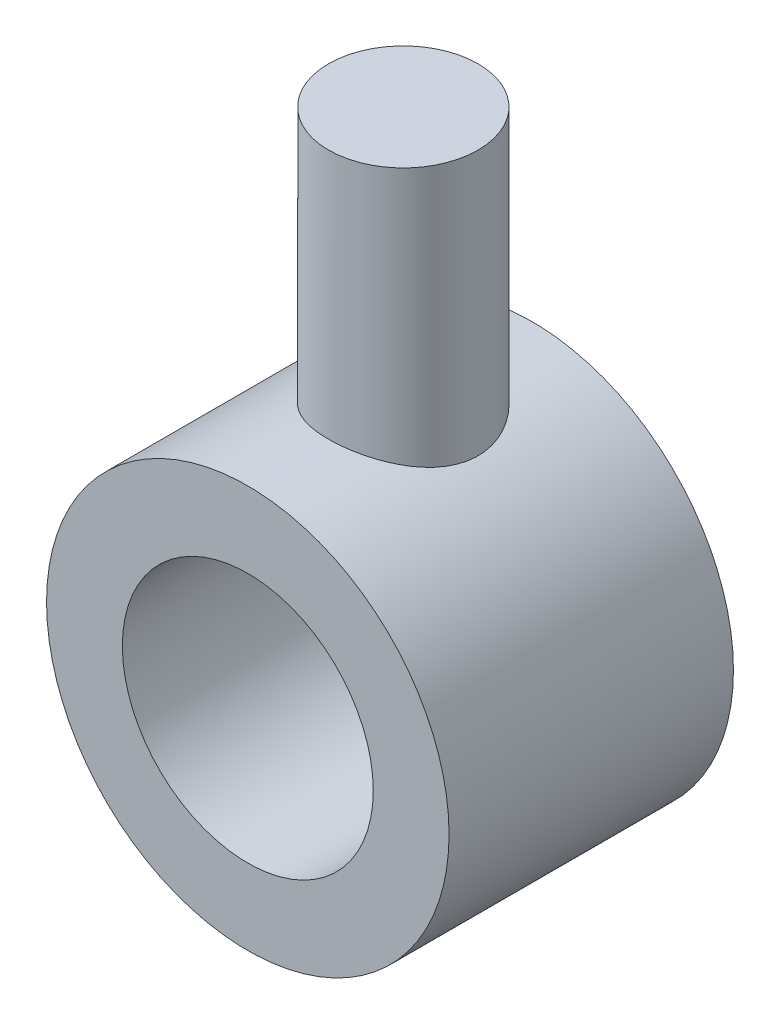
SolidWorks part; units mm, degrees
ref_plane "Front Plane" through (0, 0, 0) normal (0, 0, 1) x (1, 0, 0)
ref_plane "Top Plane" through (0, 0, 0) normal (0, 1, 0) x (1, 0, 0)
ref_plane "Right Plane" through (0, 0, 0) normal (1, 0, 0) x (0, 0, -1)
sketch "Sketch1" plane through (0, 0, 0) normal (0, 0, 1) x (1, 0, 0)
  circle A0 centre (0, 0) radius 12.0311
  circle A1 centre (0, 0) radius 7.5
  dimension "D1" = 15
  dimension "D2" = 24.0623
extrude "Boss-Extrude1" add sketch "Sketch1" along normal blind 17
ref_plane "Plane1" through (0, 10, 0) normal (0, 1, 0) x (1, 0, 0)
sketch "Sketch2" plane through (0, 10, 0) normal (0, 1, 0) x (1, 0, 0)
  circle A0 centre (0, -7.7043) radius 4.4689
  point P2 (0, 0)
extrude "Boss-Extrude2" add sketch "Sketch2" along normal blind 17
